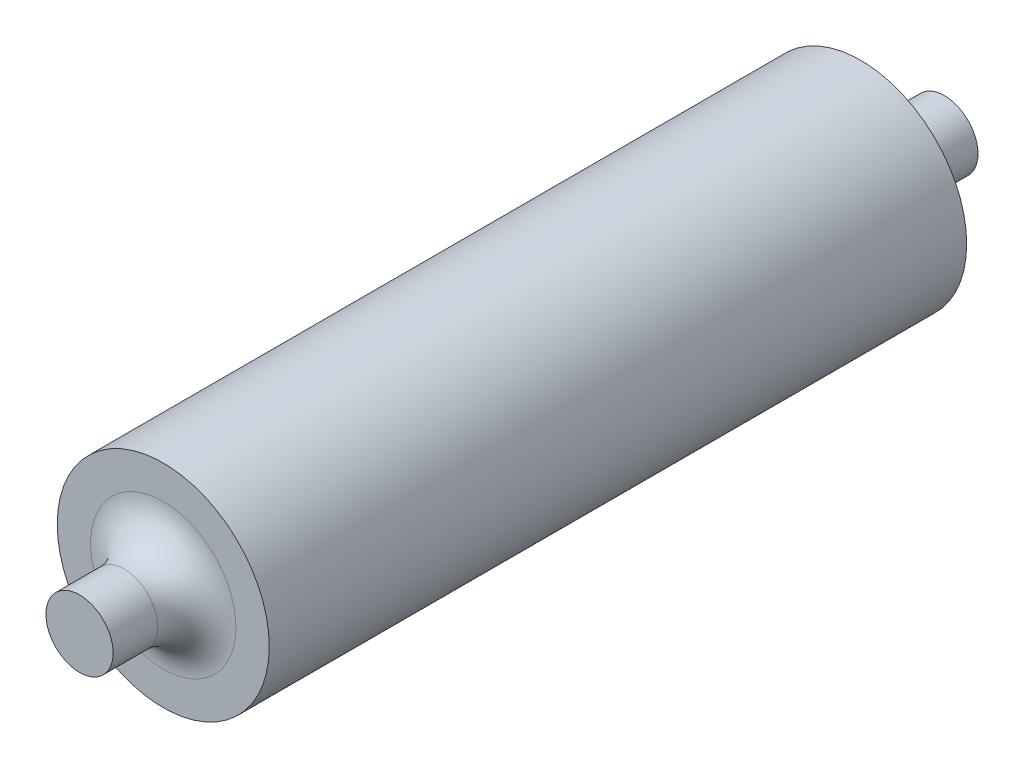
SolidWorks part; units mm, degrees
ref_plane "Front Plane" through (0, 0, 0) normal (0, 0, 1) x (1, 0, 0)
ref_plane "Top Plane" through (0, 0, 0) normal (0, 1, 0) x (1, 0, 0)
ref_plane "Right Plane" through (0, 0, 0) normal (1, 0, 0) x (0, 0, -1)
sketch "Sketch1" plane through (0, 0, 0) normal (0, 0, 1) x (1, 0, 0)
  circle A0 centre (0, 0) radius 14
  circle A1 centre (0, 0) radius 19
  dimension "D1" = 28
  dimension "D2" = 38
extrude "Boss-Extrude1" add sketch "Sketch1" against normal blind 125
ref_plane "Plane1" through (0, 0, -7.5) normal (0, 0, 1) x (1, 0, 0)
sketch "Sketch2" plane through (0, 0, -7.5) normal (0, 0, 1) x (1, 0, 0)
  circle A0 centre (0, 0) radius 14
  circle A1 centre (0, 0) radius 14 construction
extrude "Boss-Extrude2" add sketch "Sketch2" along normal up to surface (7.5 mm away) up to face at (14, 0, 0)
sketch "Sketch4" plane through (0, 0, -7.5) normal (0, 0, 1) x (1, 0, 0)
  circle A0 centre (0, 0) radius 6.025
  circle A1 centre (0, 0) radius 14 construction
  dimension "D1" = 12.05
extrude "Cut-Extrude1" cut sketch "Sketch4" against normal through all both and the other way through all
ref_plane "Plane2" through (0, 0, -117.5) normal (0, 0, -1) x (-1, 0, 0)
sketch "Sketch5" plane through (0, 0, -117.5) normal (0, 0, -1) x (-1, 0, 0)
  circle A0 centre (0, 0) radius 14
  circle A1 centre (0, 0) radius 14 construction
extrude "Boss-Extrude3" add sketch "Sketch5" along normal blind 7.5
sketch "Sketch7" plane through (0, 0, 0) normal (0, 0, 1) x (1, 0, 0)
  circle A0 centre (0, 0) radius 6.025
  circle A1 centre (0, 0) radius 6.025 construction
extrude "Boss-Extrude4" add sketch "Sketch7" along normal blind 15 and the other way blind 140
ref_plane "Plane3" through (0, 0, -62.5) normal (0, 0, 1) x (1, 0, 0)
sketch "Sketch8" plane through (0, 0, -62.5) normal (0, 0, 1) x (1, 0, 0)
  circle A0 centre (0, 0) radius 15
  dimension "D1" = 30
extrude "Boss-Extrude5" add sketch "Sketch8" along normal blind 5 and the other way blind 5
pattern_linear "LPattern2" count 2 spacing 30 along (0, 0, -1) of "Boss-Extrude5"
pattern_linear "LPattern3" count 2 spacing 30 along (0, 0, 1) of "LPattern2"
fillet "Fillet1" radius 7 2 edges at (6.025, 0, 0) (6.025, 0, -125)
